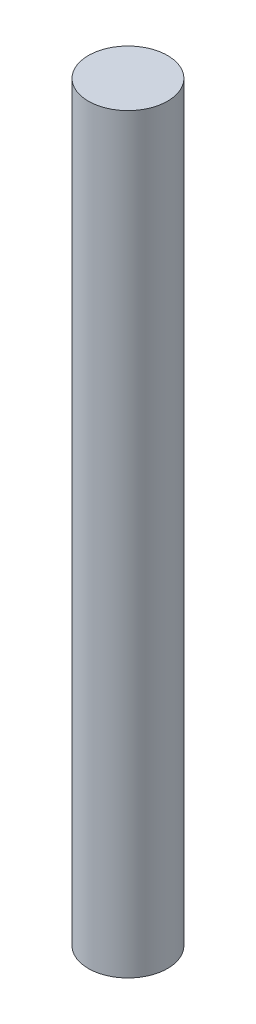
SolidWorks part; units mm, degrees
material "Custom Plastic"
ref_plane "Alzado" through (0, 0, 0) normal (0, 0, 1) x (1, 0, 0)
ref_plane "Planta" through (0, 0, 0) normal (0, 1, 0) x (1, 0, 0)
ref_plane "Vista lateral" through (0, 0, 0) normal (1, 0, 0) x (0, 0, -1)
sketch "Sketch1" plane through (0, 0, 0) normal (0, 1, 0) x (1, 0, 0)
  circle A0 centre (0, 0) radius 1.95
  dimension "D1" = 3.9
extrude "Boss-Extrude1" add sketch "Sketch1" along normal blind 37
